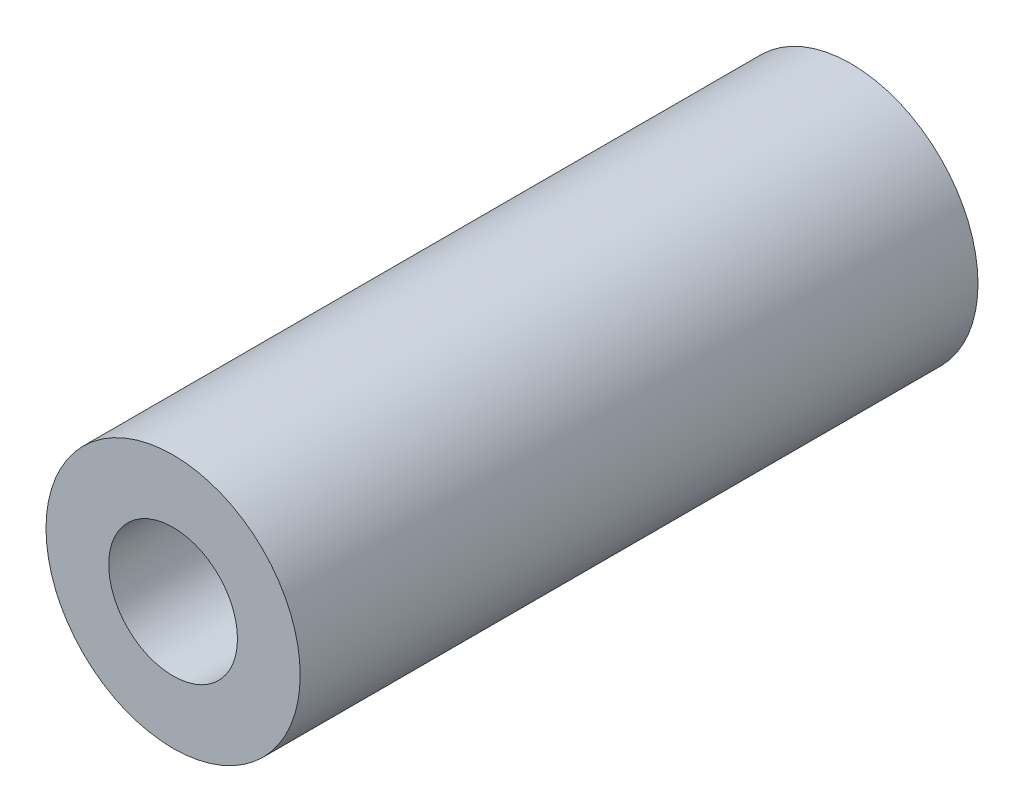
SolidWorks part; units mm, degrees
ref_plane "Front Plane" through (0, 0, 0) normal (0, 0, 1) x (1, 0, 0)
ref_plane "Top Plane" through (0, 0, 0) normal (0, 1, 0) x (1, 0, 0)
ref_plane "Right Plane" through (0, 0, 0) normal (1, 0, 0) x (0, 0, -1)
sketch "Sketch2" plane through (0, 0, 0) normal (0, 0, 1) x (1, 0, 0)
  circle A0 centre (0, 0) radius 9.525
  circle A1 centre (0, 0) radius 4.826
  dimension "D1" = 19.05
  dimension "D2" = 9.652
extrude "Boss-Extrude1" add sketch "Sketch2" along normal blind 50.8
